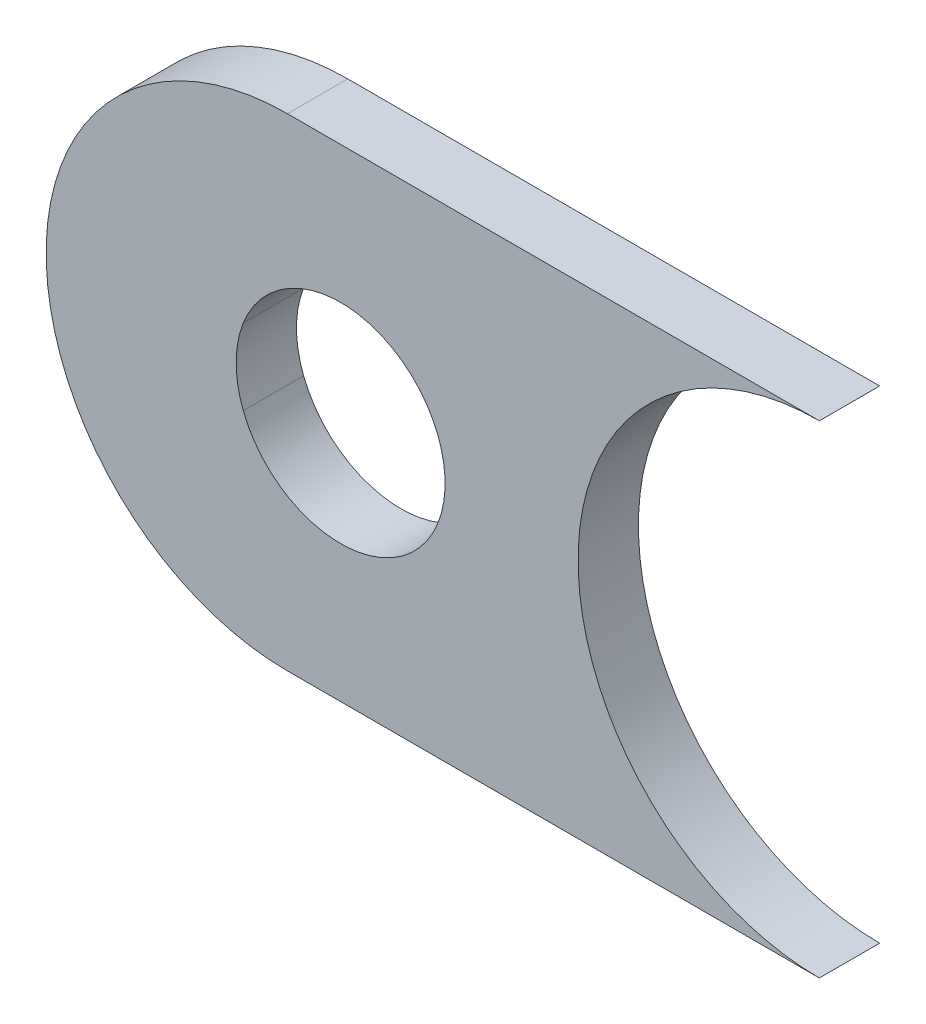
SolidWorks part; units mm, degrees
material "AISI 4340 Steel, annealed"
ref_plane "Front Plane" through (0, 0, 0) normal (0, 0, 1) x (1, 0, 0)
ref_plane "Top Plane" through (0, 0, 0) normal (0, 1, 0) x (1, 0, 0)
ref_plane "Right Plane" through (0, 0, 0) normal (1, 0, 0) x (0, 0, -1)
sketch "Sketch2" plane through (0, 0, 0) normal (0, 0, 1) x (1, 0, 0)
  line L0 (0, 12.7) -> (-28, 12.7)
  line L1 (0, -12.7) -> (-28, -12.7)
  line L2 (-19.7, 0) -> (-12.7, 0) construction
  line L3 (-40.7, 0) -> (-30.7, 0) construction
  circle A0 centre (0, 0) radius 12.7
  arc A1 (-28, 12.7) -> (-28, -12.7) centre (-28, 0) ccw
  circle A3 centre (-25.2, 0) radius 5.5
  dimension "D1" = 25.4
  dimension "D2" = 11
  dimension "D3" = 10
  dimension "D4" = 7
extrude "Boss-Extrude1" add sketch "Sketch2" along normal blind 3.175 contours L0 A1 L1 A0 A3
ref_plane "Plane1" through (-30.7, 0, 0) normal (1, 0, 0) x (0, 0, -1)
sketch "Sketch4" plane through (-30.7, 0, 0) normal (1, 0, 0) x (0, 0, -1)
  line L0 (1.7463, 0) -> (-1.7463, 0) construction
  line L1 (1.0975, -2) -> (-4.2699, -2)
  line L2 (1.0975, -2) -> (1.0975, 2)
  line L3 (1.0975, 2) -> (-4.2699, 2)
  line L4 (-4.2699, -2) -> (-4.2699, 2)
  line L5 (1.0975, -2) -> (-4.2699, 2) construction
  line L6 (1.0975, 2) -> (-4.2699, -2) construction
  point P0 (-1.5862, 0)
  dimension "D1" = 4
split line "Split Line1"
